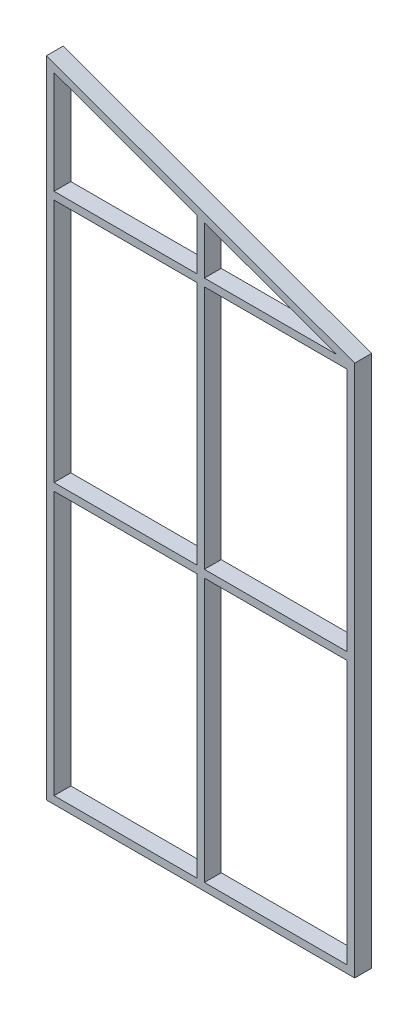
SolidWorks part; units mm, degrees
ref_plane "Plan de face" through (0, 0, 0) normal (0, 0, 1) x (1, 0, 0)
ref_plane "Plan de dessus" through (0, 0, 0) normal (0, 1, 0) x (1, 0, 0)
ref_plane "Plan de droite" through (0, 0, 0) normal (1, 0, 0) x (0, 0, -1)
sketch "Esquisse1" plane through (0, 0, 0) normal (0, 0, 1) x (1, 0, 0)
  line L0 (0, 0) -> (1100, 0)
  line L1 (1100, 0) -> (1100, 1900)
  line L2 (1100, 1900) -> (0, 2300)
  line L3 (0, 2300) -> (0, 0)
  line L4 (27, 27) -> (1073, 27)
  line L5 (1073, 27) -> (1073, 1881.0885)
  line L6 (1073, 1881.0885) -> (27, 2261.4521)
  line L7 (27, 2261.4521) -> (27, 27)
  dimension "D1" = 1100
  dimension "D2" = 2300
  dimension "D3" = 1900
  dimension "D4" = 27
extrude "Boss.-Extru.1" add sketch "Esquisse1" along normal blind 60
sketch "Esquisse2" plane through (0, 0, 60) normal (0, 0, 1) x (1, 0, 0)
  line L0 (550, 27) -> (550, 2090)
  line L1 (27, 27) -> (1073, 27) construction
  line L2 (550, 2090) -> (550, 2100) construction
  line L3 (1100, 1900) -> (0, 2300) construction
  line L4 (1073, 1881.0885) -> (27, 1881.0885)
  line L5 (27, 2261.4521) -> (27, 27) construction
  line L6 (27, 981.0885) -> (1073, 981.0885)
  line L7 (1073, 27) -> (1073, 1881.0885) construction
  dimension "D1" = 10
  dimension "D2" = 900
extrude "Extru.-Mince1" add sketch "Esquisse2" against normal blind 60 thin thin type mid plane wall 27
